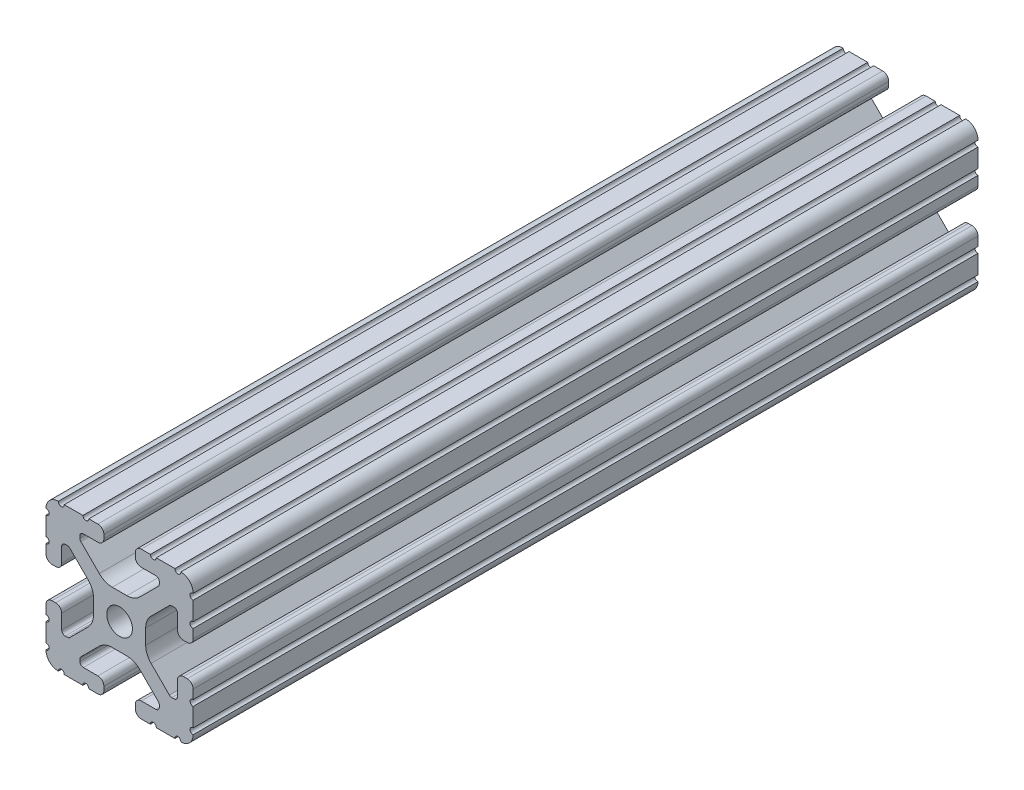
SolidWorks part; units mm, degrees
material "6061 Alloy"
ref_plane "Front Plane" through (0, 0, 0) normal (0, 0, 1) x (1, 0, 0)
ref_plane "Top Plane" through (0, 0, 0) normal (0, 1, 0) x (1, 0, 0)
ref_plane "Right Plane" through (0, 0, 0) normal (1, 0, 0) x (0, 0, -1)
sketch "Sketch1" plane through (0, 0, 0) normal (0, 0, 1) x (1, 0, 0)
  line L0 (0, 25.6181) -> (0, -24.623) construction
  line L1 (-20.8943, 0) -> (20.4607, 0) construction
  line L2 (-10.0229, 12.9148) -> (-5.2522, 8.144)
  line L3 (-10.287, 14.0843) -> (-10.287, 13.5524)
  line L4 (-5.6176, 14.986) -> (-9.3853, 14.986)
  line L5 (-4.064, 17.4964) -> (-4.064, 16.5396)
  line L6 (-7.9742, 19.05) -> (-5.6176, 19.05)
  line L7 (-14.3277, 19.05) -> (-9.4982, 19.05)
  line L8 (-19.05, 9.4961) -> (-19.05, 14.3277)
  line L9 (-19.05, 5.6176) -> (-19.05, 7.9763)
  line L10 (-16.5396, 4.064) -> (-17.4964, 4.064)
  line L11 (-14.986, 9.3853) -> (-14.986, 5.6176)
  line L12 (-13.516, 10.287) -> (-14.0843, 10.287)
  line L13 (-8.1476, 5.2921) -> (-12.8784, 10.0229)
  line L14 (-6.7564, -1.9335) -> (-6.7564, 1.9335)
  line L15 (-12.8784, -10.0229) -> (-8.1476, -5.2921)
  line L16 (-14.0843, -10.287) -> (-13.516, -10.287)
  line L17 (-14.986, -5.6176) -> (-14.986, -9.3853)
  line L18 (-17.4964, -4.064) -> (-16.5396, -4.064)
  line L19 (-19.05, -7.9763) -> (-19.05, -5.6176)
  line L20 (-19.05, -14.3277) -> (-19.05, -9.4961)
  line L21 (-9.4961, -19.05) -> (-14.3277, -19.05)
  line L22 (-5.6176, -19.05) -> (-7.9763, -19.05)
  line L23 (-4.064, -17.4964) -> (-4.064, -16.5396)
  line L24 (10.0229, -12.9148) -> (5.2522, -8.144)
  line L25 (10.287, -14.0843) -> (10.287, -13.5524)
  line L26 (5.6176, -14.986) -> (9.3853, -14.986)
  line L28 (-1.9022, 6.7564) -> (1.9022, 6.7564)
  line L29 (-1.9022, -6.7564) -> (1.9022, -6.7564)
  line L31 (-5.6176, -14.986) -> (-9.3853, -14.986)
  line L32 (-10.287, -14.0843) -> (-10.287, -13.5524)
  line L33 (-10.0229, -12.9148) -> (-5.2522, -8.144)
  line L66 (4.064, -16.5396) -> (4.064, -17.4964)
  line L67 (5.6176, -19.05) -> (7.9763, -19.05)
  line L68 (9.4961, -19.05) -> (14.3277, -19.05)
  line L69 (19.05, -14.3277) -> (19.05, -9.4961)
  line L70 (19.05, -7.9763) -> (19.05, -5.6176)
  line L71 (17.4964, -4.064) -> (16.5396, -4.064)
  line L72 (14.986, -5.6176) -> (14.986, -9.3853)
  line L73 (14.0843, -10.287) -> (13.516, -10.287)
  line L74 (12.8784, -10.0229) -> (8.1476, -5.2921)
  line L75 (6.7564, -1.9335) -> (6.7564, 1.9335)
  line L76 (8.1476, 5.2921) -> (12.8784, 10.0229)
  line L77 (13.516, 10.287) -> (14.0843, 10.287)
  line L78 (14.986, 9.3853) -> (14.986, 5.6176)
  line L79 (16.5396, 4.064) -> (17.4964, 4.064)
  line L80 (19.05, 5.6176) -> (19.05, 7.9763)
  line L81 (19.05, 9.4961) -> (19.05, 14.3277)
  line L82 (14.3277, 19.05) -> (9.4982, 19.05)
  line L83 (7.9742, 19.05) -> (5.6176, 19.05)
  line L84 (4.064, 17.4964) -> (4.064, 16.5396)
  line L85 (5.6176, 14.986) -> (9.3853, 14.986)
  line L86 (10.287, 14.0843) -> (10.287, 13.5524)
  line L87 (10.0229, 12.9148) -> (5.2522, 8.144)
  arc A0 (-10.0229, 12.9148) -> (-10.287, 13.5524) centre (-9.3853, 13.5524) cw
  circle A1 centre (0, 0) radius 3.3274
  arc A2 (-10.287, 14.0843) -> (-9.3853, 14.986) centre (-9.3853, 14.0843) cw
  arc A3 (-4.064, 16.5396) -> (-5.6176, 14.986) centre (-5.6176, 16.5396) cw
  arc A4 (-5.6176, 19.05) -> (-4.064, 17.4964) centre (-5.6176, 17.4964) cw
  arc A5 (-7.9742, 19.05) -> (-9.4982, 19.05) centre (-8.7362, 19.05) cw
  arc A6 (-14.3277, 19.05) -> (-15.8475, 19.05) centre (-15.0876, 18.9933) cw
  arc A7 (-19.05, 15.8475) -> (-15.8475, 19.05) centre (-15.8751, 15.8751) cw
  arc A8 (-19.05, 15.8475) -> (-19.05, 14.3277) centre (-18.9933, 15.0876) cw
  arc A9 (-19.05, 9.4961) -> (-19.05, 7.9763) centre (-18.9933, 8.7362) cw
  arc A10 (-17.4964, 4.064) -> (-19.05, 5.6176) centre (-17.4964, 5.6176) cw
  arc A11 (-14.986, 5.6176) -> (-16.5396, 4.064) centre (-16.5396, 5.6176) cw
  arc A12 (-14.986, 9.3853) -> (-14.0843, 10.287) centre (-14.0843, 9.3853) cw
  arc A13 (-13.516, 10.287) -> (-12.8784, 10.0229) centre (-13.516, 9.3853) cw
  arc A14 (-8.1476, 5.2921) -> (-6.7564, 1.9335) centre (-11.5062, 1.9335) cw
  arc A15 (-6.7564, -1.9335) -> (-8.1476, -5.2921) centre (-11.5062, -1.9335) cw
  arc A16 (-12.8784, -10.0229) -> (-13.516, -10.287) centre (-13.516, -9.3853) cw
  arc A17 (-14.0843, -10.287) -> (-14.986, -9.3853) centre (-14.0843, -9.3853) cw
  arc A18 (-16.5396, -4.064) -> (-14.986, -5.6176) centre (-16.5396, -5.6176) cw
  arc A19 (-19.05, -5.6176) -> (-17.4964, -4.064) centre (-17.4964, -5.6176) cw
  arc A20 (-19.05, -7.9763) -> (-19.05, -9.4961) centre (-18.9933, -8.7362) cw
  arc A21 (-19.05, -14.3277) -> (-19.05, -15.8475) centre (-18.9933, -15.0876) cw
  arc A22 (-15.8475, -19.05) -> (-19.05, -15.8475) centre (-15.8751, -15.8751) cw
  arc A23 (-15.8475, -19.05) -> (-14.3277, -19.05) centre (-15.0876, -18.9933) cw
  arc A24 (-9.4961, -19.05) -> (-7.9763, -19.05) centre (-8.7362, -18.9933) cw
  arc A25 (-4.064, -17.4964) -> (-5.6176, -19.05) centre (-5.6176, -17.4964) cw
  arc A26 (-5.2522, -8.144) -> (-1.9022, -6.7564) centre (-1.9022, -11.494) cw
  arc A27 (1.9022, -6.7564) -> (5.2522, -8.144) centre (1.9022, -11.494) cw
  arc A28 (10.0229, -12.9148) -> (10.287, -13.5524) centre (9.3853, -13.5524) cw
  arc A29 (10.287, -14.0843) -> (9.3853, -14.986) centre (9.3853, -14.0843) cw
  arc A30 (4.064, -16.5396) -> (5.6176, -14.986) centre (5.6176, -16.5396) cw
  arc A31 (-4.064, -16.5396) -> (-5.6176, -14.986) centre (-5.6176, -16.5396) ccw
  arc A32 (-10.287, -14.0843) -> (-9.3853, -14.986) centre (-9.3853, -14.0843) ccw
  arc A33 (-10.0229, -12.9148) -> (-10.287, -13.5524) centre (-9.3853, -13.5524) ccw
  arc A79 (4.064, -17.4964) -> (5.6176, -19.05) centre (5.6176, -17.4964) ccw
  arc A80 (9.4961, -19.05) -> (7.9763, -19.05) centre (8.7362, -18.9933) ccw
  arc A81 (15.8475, -19.05) -> (14.3277, -19.05) centre (15.0876, -18.9933) ccw
  arc A82 (15.8475, -19.05) -> (19.05, -15.8475) centre (15.8751, -15.8751) ccw
  arc A83 (19.05, -14.3277) -> (19.05, -15.8475) centre (18.9933, -15.0876) ccw
  arc A84 (19.05, -7.9763) -> (19.05, -9.4961) centre (18.9933, -8.7362) ccw
  arc A85 (19.05, -5.6176) -> (17.4964, -4.064) centre (17.4964, -5.6176) ccw
  arc A86 (16.5396, -4.064) -> (14.986, -5.6176) centre (16.5396, -5.6176) ccw
  arc A87 (14.0843, -10.287) -> (14.986, -9.3853) centre (14.0843, -9.3853) ccw
  arc A88 (12.8784, -10.0229) -> (13.516, -10.287) centre (13.516, -9.3853) ccw
  arc A89 (6.7564, -1.9335) -> (8.1476, -5.2921) centre (11.5062, -1.9335) ccw
  arc A90 (8.1476, 5.2921) -> (6.7564, 1.9335) centre (11.5062, 1.9335) ccw
  arc A91 (13.516, 10.287) -> (12.8784, 10.0229) centre (13.516, 9.3853) ccw
  arc A92 (14.986, 9.3853) -> (14.0843, 10.287) centre (14.0843, 9.3853) ccw
  arc A93 (14.986, 5.6176) -> (16.5396, 4.064) centre (16.5396, 5.6176) ccw
  arc A94 (17.4964, 4.064) -> (19.05, 5.6176) centre (17.4964, 5.6176) ccw
  arc A95 (19.05, 9.4961) -> (19.05, 7.9763) centre (18.9933, 8.7362) ccw
  arc A96 (19.05, 15.8475) -> (19.05, 14.3277) centre (18.9933, 15.0876) ccw
  arc A97 (19.05, 15.8475) -> (15.8475, 19.05) centre (15.8751, 15.8751) ccw
  arc A98 (14.3277, 19.05) -> (15.8475, 19.05) centre (15.0876, 18.9933) ccw
  arc A99 (7.9742, 19.05) -> (9.4982, 19.05) centre (8.7362, 19.05) ccw
  arc A100 (5.6176, 19.05) -> (4.064, 17.4964) centre (5.6176, 17.4964) ccw
  arc A101 (4.064, 16.5396) -> (5.6176, 14.986) centre (5.6176, 16.5396) ccw
  arc A102 (10.287, 14.0843) -> (9.3853, 14.986) centre (9.3853, 14.0843) ccw
  arc A103 (10.0229, 12.9148) -> (10.287, 13.5524) centre (9.3853, 13.5524) ccw
  arc A104 (1.9022, 6.7564) -> (5.2522, 8.144) centre (1.9022, 11.494) ccw
  arc A105 (-5.2522, 8.144) -> (-1.9022, 6.7564) centre (-1.9022, 11.494) ccw
  dimension "D1" = 6.6548
  dimension "D2" = 19.05
  dimension "D3" = 38.1
  dimension "D4" = 20.574
  dimension "D5" = 13.5128
  dimension "D6" = 4.064
  dimension "D7" = 8.128
  dimension "D8" = 4.064
  dimension "D9" = 12.2936
extrude "Extrude1" add sketch "Sketch1" against normal blind 203.2
